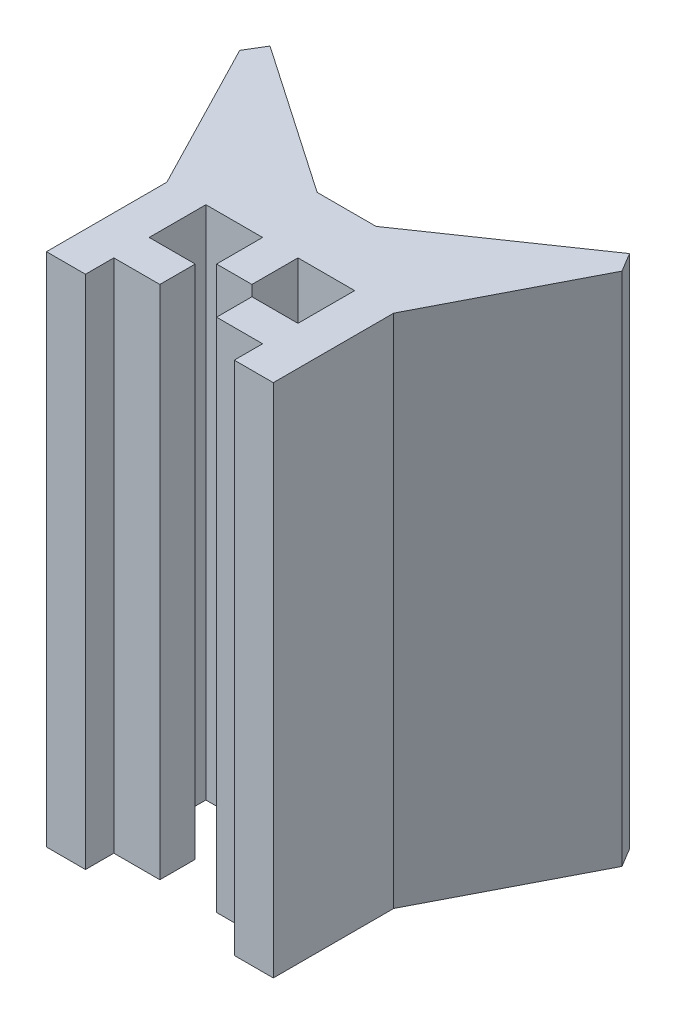
SolidWorks part; units mm, degrees
ref_plane "Plan de face" through (0, 0, 0) normal (0, 0, 1) x (1, 0, 0)
ref_plane "Plan de dessus" through (0, 0, 0) normal (0, 1, 0) x (1, 0, 0)
ref_plane "Plan de droite" through (0, 0, 0) normal (1, 0, 0) x (0, 0, -1)
sketch "Base" plane through (0, 0, 0) normal (0, 1, 0) x (1, 0, 0)
  line L0 (-3.85, -2.4) -> (-3.85, 2.4)
  line L1 (-3.85, 2.4) -> (-10.1, 2.4)
  line L2 (-10.1, 2.4) -> (-10.1, 10.1)
  line L3 (-10.1, 10.1) -> (-2.4, 10.1)
  line L4 (-2.4, 10.1) -> (-2.4, 3.85)
  line L5 (-2.4, 3.85) -> (2.4, 3.85)
  line L6 (0, -24.6801) -> (0, 24.6801) construction
  line L7 (2.4, 10.1) -> (2.4, 3.85)
  line L8 (10.1, 10.1) -> (2.4, 10.1)
  line L9 (10.1, 2.4) -> (10.1, 10.1)
  line L10 (3.85, 2.4) -> (10.1, 2.4)
  line L11 (3.85, -2.4) -> (3.85, 2.4)
  line L12 (-28.5456, 0) -> (28.5456, 0) construction
  line L13 (3.85, -2.4) -> (10.1, -2.4)
  line L14 (10.1, -2.4) -> (10.1, -6.2477)
  line L20 (-10.1, -2.4) -> (-10.1, -6.2477)
  line L21 (-3.85, -2.4) -> (-10.1, -2.4)
  line L24 (-15.4, 10.1023) -> (-15.4, -6.2477)
  line L26 (15.4, 10.1023) -> (15.4, -6.2477)
  line L29 (-10.1, -6.2477) -> (-15.4, -6.2477)
  line L30 (10.1, -6.2477) -> (15.4, -6.2477)
  line L32 (-25.9505, 30.5397) -> (-15.4, 10.1023)
  line L33 (0, 0) -> (0, 38.6251) construction
  line L34 (24.4075, 33.1124) -> (4, 19.1023)
  line L35 (4, 19.1023) -> (-4, 19.1023)
  line L36 (-24.4075, 33.1124) -> (-4, 19.1023)
  line L38 (25.9505, 30.5397) -> (15.4, 10.1023)
  line L42 (24.4075, 33.1124) -> (25.9505, 30.5397)
  line L43 (-24.4075, 33.1124) -> (-25.9505, 30.5397)
  point P2 (-3.85, 0)
  point P3 (0, 3.85)
  point P27 (0, 0)
  point P38 (0, 19.1023)
  dimension "D6" = 24.7538
  dimension "D1" = 4.8
  dimension "D2" = 4.8
  dimension "D3" = 6.25
  dimension "D4" = 7.7
  dimension "D5" = 23
  dimension "D7" = 9
  dimension "D9" = 16.35
  dimension "D10" = 8
  dimension "D11" = 3
  dimension "D12" = 5.3
extrude "Boss.-Extru.2" add sketch "Base" along normal blind 70 contours L34 L35 L36 L43 L32 L24 L29 L20 L21 L0 L1 L2 L3 L4 L5 L7 L8 L9 L10 L11 L13 L14 L30 L26 L38 L42
